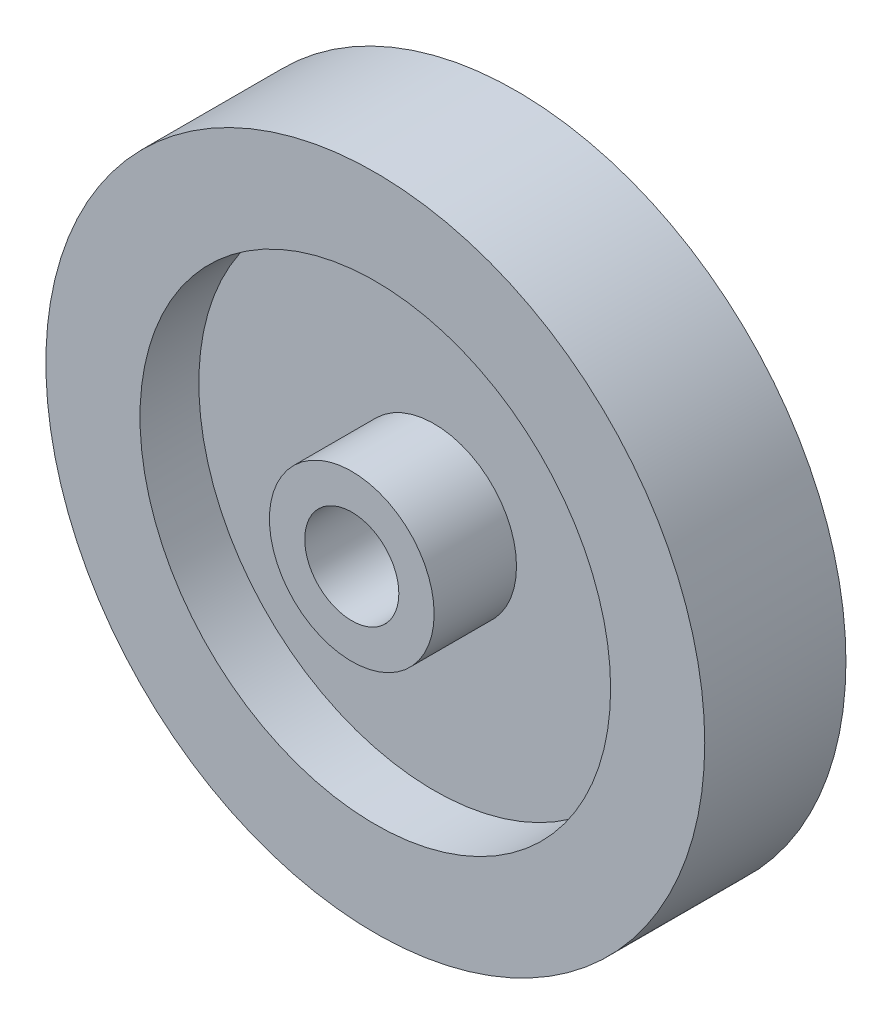
SolidWorks part; units mm, degrees
ref_plane "Front Plane" through (0, 0, 0) normal (0, 0, 1) x (1, 0, 0)
ref_plane "Top Plane" through (0, 0, 0) normal (0, 1, 0) x (1, 0, 0)
ref_plane "Right Plane" through (0, 0, 0) normal (1, 0, 0) x (0, 0, -1)
sketch "Sketch1" plane through (0, 0, 0) normal (1, 0, 0) x (0, 0, -1)
  line L0 (0, 0) -> (0, 130.3734) construction
  line L1 (0, 0) -> (71.4556, 0) construction
  line L2 (-25.4, 12.7) -> (25.4, 12.7)
  line L3 (-25.4, 12.7) -> (-25.4, 22.225)
  line L4 (-25.4, 22.225) -> (-3.175, 22.225)
  line L5 (25.4, 12.7) -> (25.4, 22.225)
  line L6 (-25.4, 12.7) -> (25.4, 22.225) construction
  line L7 (-25.4, 22.225) -> (25.4, 12.7) construction
  line L8 (-19.05, 88.9) -> (19.05, 88.9)
  line L9 (-19.05, 88.9) -> (-19.05, 63.5)
  line L10 (-19.05, 63.5) -> (-3.175, 63.5)
  line L11 (19.05, 88.9) -> (19.05, 63.5)
  line L12 (-19.05, 88.9) -> (19.05, 63.5) construction
  line L13 (-19.05, 63.5) -> (19.05, 88.9) construction
  line L19 (-3.175, 22.225) -> (-3.175, 63.5)
  line L21 (3.175, 22.225) -> (3.175, 63.5)
  line L22 (3.175, 63.5) -> (19.05, 63.5)
  line L23 (3.175, 22.225) -> (25.4, 22.225)
  point P3 (0, 17.4625)
  point P8 (0, 76.2)
  dimension "D1" = 38.1
  dimension "D2" = 50.8
  dimension "D3" = 25.4
  dimension "D4" = 6.35
  dimension "D5" = 44.45
  dimension "D6" = 127
  dimension "D7" = 177.8
revolve "Revolve2" add sketch "Sketch1" angle 360 about L1
sketch "Sketch2" plane through (0, 0, 0) normal (1, 0, 0) x (0, 0, -1)
  line L0 (0, 88.9) -> (0, 72.999) construction
  line L1 (19.05, 88.9) -> (-19.05, 88.9) construction
  line L2 (-10.9724, 88.687) -> (-6.35, 75.987)
  line L3 (-6.35, 75.987) -> (6.35, 75.987)
  line L4 (6.35, 75.987) -> (10.9724, 88.687)
  line L5 (10.9724, 88.687) -> (-10.9724, 88.687)
  line L6 (0, 0) -> (87.7987, 0) construction
  dimension "D1" = 40
  dimension "D2" = 12.7
  dimension "D3" = 12.7
revolve "Cut-Revolve1" cut sketch "Sketch2" angle 360 about L6
